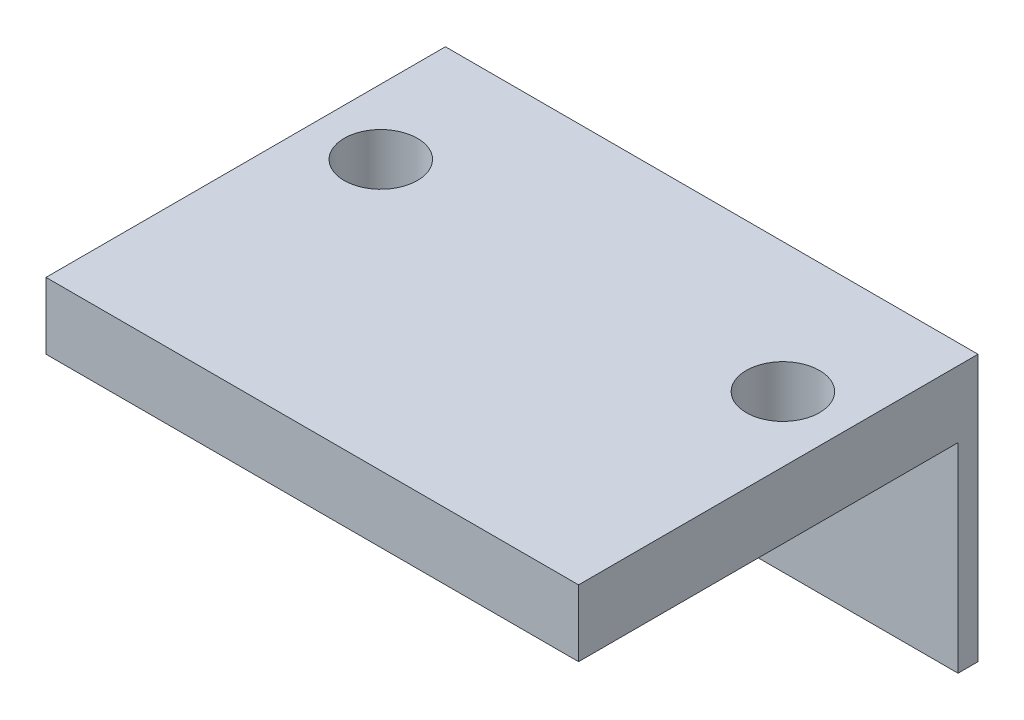
SolidWorks part; units mm, degrees
ref_plane "Front Plane" through (0, 0, 0) normal (0, 0, 1) x (1, 0, 0)
ref_plane "Top Plane" through (0, 0, 0) normal (0, 1, 0) x (1, 0, 0)
ref_plane "Right Plane" through (0, 0, 0) normal (1, 0, 0) x (0, 0, -1)
sketch "Sketch1" plane through (0, 0, 0) normal (0, 1, 0) x (1, 0, 0)
  line L1 (-35, -35) -> (45, -35)
  line L2 (-35, -35) -> (-35, 25)
  line L3 (-35, 25) -> (45, 25)
  line L4 (45, -35) -> (45, 25)
  point P0 (0, 0)
  dimension "D1" = 60
  dimension "D2" = 80
extrude "Boss-Extrude1" add sketch "Sketch1" along normal blind 10
sketch "Sketch2" plane through (0, 10, 0) normal (0, 1, 0) x (1, 0, 0)
  line L0 (-35, 25) -> (-35, -35) construction
  line L1 (45, -35) -> (45, 25) construction
  line L3 (45, 25) -> (-35, 25) construction
  circle A0 centre (-25.2003, 5.4913) radius 5.5
  circle A1 centre (35.2, 5.4913) radius 5.5
  dimension "D1" = 11
  dimension "D2" = 9.7997
  dimension "D3" = 9.8
  dimension "D4" = 19.5087
  dimension "D5" = 19.5087
extrude "Cut-Extrude1" cut sketch "Sketch2" against normal through all
sketch "Sketch3" plane through (0, 0, 0) normal (0, -1, 0) x (1, 0, 0)
  line L0 (45, -25) -> (45, -22)
  line L1 (45, -25) -> (-34.9995, -25)
  line L2 (45, -22) -> (-34.9995, -22)
  line L3 (-34.9995, -25) -> (-34.9995, -22)
  line L4 (45, 35) -> (45, -25) construction
extrude "Boss-Extrude2" add sketch "Sketch3" along normal blind 30
